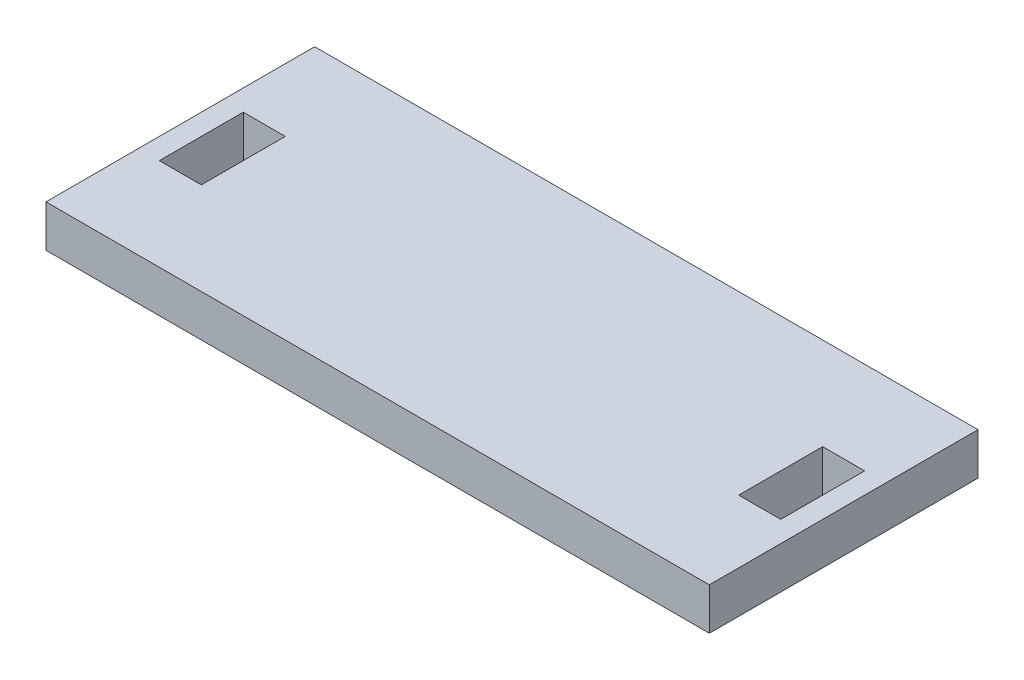
SolidWorks part; units mm, degrees
ref_plane "Front Plane" through (0, 0, 0) normal (0, 0, 1) x (1, 0, 0)
ref_plane "Top Plane" through (0, 0, 0) normal (0, 1, 0) x (1, 0, 0)
ref_plane "Right Plane" through (0, 0, 0) normal (1, 0, 0) x (0, 0, -1)
sketch "Sketch1" plane through (0, 0, 0) normal (0, 1, 0) x (1, 0, 0)
  line L0 (-25.0825, 0) -> (25.0825, 0) construction
  line L1 (-25.0825, -10.16) -> (25.0825, -10.16)
  line L2 (-25.0825, -10.16) -> (-25.0825, 10.16)
  line L3 (-25.0825, 10.16) -> (25.0825, 10.16)
  line L4 (25.0825, -10.16) -> (25.0825, 10.16)
  line L5 (-25.0825, -10.16) -> (25.0825, 10.16) construction
  line L6 (-25.0825, 10.16) -> (25.0825, -10.16) construction
  line L8 (-23.495, -3.175) -> (-20.32, -3.175)
  line L9 (-23.495, -3.175) -> (-23.495, 3.175)
  line L10 (-23.495, 3.175) -> (-20.32, 3.175)
  line L11 (-20.32, -3.175) -> (-20.32, 3.175)
  line L12 (-23.495, -3.175) -> (-20.32, 3.175) construction
  line L13 (-23.495, 3.175) -> (-20.32, -3.175) construction
  line L14 (20.32, -3.175) -> (23.495, -3.175)
  line L15 (20.32, -3.175) -> (20.32, 3.175)
  line L16 (20.32, 3.175) -> (23.495, 3.175)
  line L17 (23.495, -3.175) -> (23.495, 3.175)
  line L18 (20.32, -3.175) -> (23.495, 3.175) construction
  line L19 (20.32, 3.175) -> (23.495, -3.175) construction
  point P0 (0, 0)
  point P8 (-21.9075, 0)
  point P13 (21.9075, 0)
  dimension "D1" = 50.165
  dimension "D2" = 20.32
  dimension "D3" = 3.175
  dimension "D4" = 6.35
  dimension "D5" = 1.5875
  dimension "D6" = 1.5875
  dimension "D7" = 3.175
  dimension "D8" = 6.35
extrude "Boss-Extrude1" add sketch "Sketch1" along normal blind 3.175
